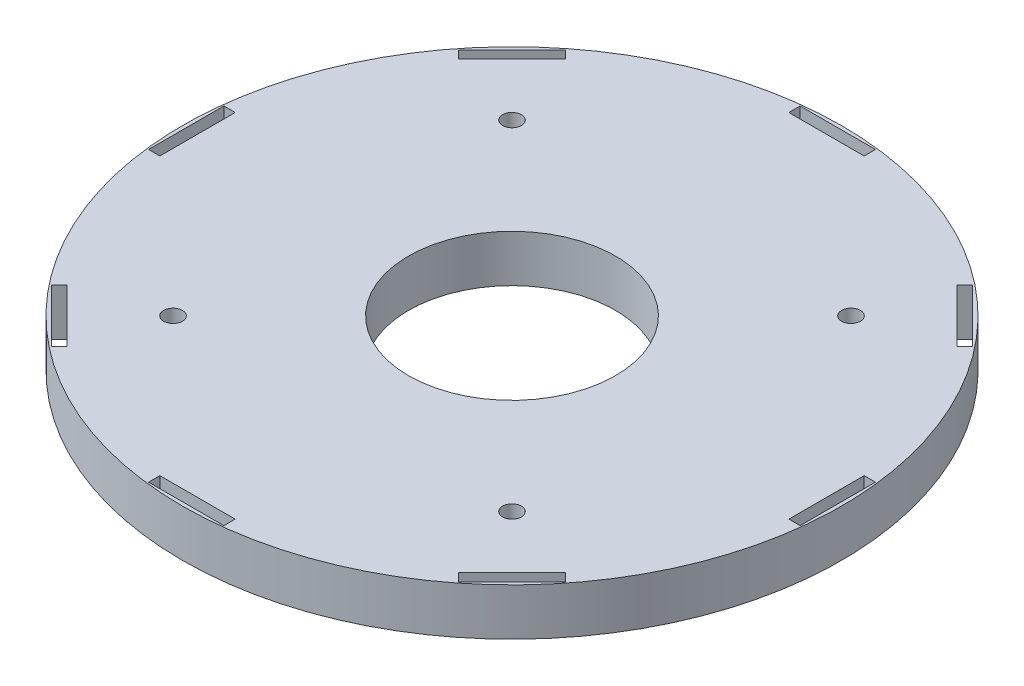
SolidWorks part; units mm, degrees
ref_plane "Front Plane" through (0, 0, 0) normal (0, 0, 1) x (1, 0, 0)
ref_plane "Top Plane" through (0, 0, 0) normal (0, 1, 0) x (1, 0, 0)
ref_plane "Right Plane" through (0, 0, 0) normal (1, 0, 0) x (0, 0, -1)
sketch "Sketch1" plane through (0, 0, 0) normal (0, 1, 0) x (1, 0, 0)
  circle A0 centre (0, 0) radius 175
  circle A1 centre (0, 0) radius 55
  dimension "D1" = 350
  dimension "D2" = 110
extrude "Boss-Extrude1" add sketch "Sketch1" along normal mid plane 25
sketch "Sketch2" plane through (0, 12.5, 0) normal (0, 1, 0) x (1, 0, 0)
  line L0 (0, 257.3432) -> (0, -227.7607) construction
  line L1 (-310.3726, 0) -> (339.0303, 0) construction
  line L3 (-20, 173) -> (20, 173)
  line L4 (-20, 173) -> (-20, 167)
  line L5 (-20, 167) -> (20, 167)
  line L6 (20, 173) -> (20, 167)
  line L7 (-20, 173) -> (20, 167) construction
  line L8 (-20, 167) -> (20, 173) construction
  line L30 (-160.5, -7.5) -> (-154.5, -7.5)
  line L31 (-160.5, 32.5) -> (-154.5, 32.5)
  line L36 (-160.5, -7.5) -> (-160.5, 32.5) [skipped]
  line L37 (-154.5, -7.5) -> (-154.5, 32.5) [skipped]
  line L38 (20, -142) -> (-20, -142) [skipped]
  line L39 (20, -148) -> (-20, -148) [skipped]
  line L40 (20, -148) -> (20, -142) [skipped]
  line L41 (-20, -148) -> (-20, -142) [skipped]
  line L42 (-95.1059, -110.8901) -> (-123.3901, -82.6059) [skipped]
  line L43 (-99.3485, -115.1328) -> (-127.6328, -86.8485) [skipped]
  line L44 (-99.3485, -115.1328) -> (-95.1059, -110.8901) [skipped]
  line L45 (-127.6328, -86.8485) -> (-123.3901, -82.6059) [skipped]
  line L46 (154.5, 32.5) -> (154.5, -7.5) [skipped]
  line L47 (160.5, 32.5) -> (160.5, -7.5) [skipped]
  line L48 (160.5, 32.5) -> (154.5, 32.5) [skipped]
  line L49 (160.5, -7.5) -> (154.5, -7.5) [skipped]
  line L50 (123.3901, -82.6059) -> (95.1059, -110.8901) [skipped]
  line L51 (127.6328, -86.8485) -> (99.3485, -115.1328) [skipped]
  line L52 (127.6328, -86.8485) -> (123.3901, -82.6059) [skipped]
  line L53 (99.3485, -115.1328) -> (95.1059, -110.8901) [skipped]
  line L54 (-123.3901, 107.6059) -> (-95.1059, 135.8901) [skipped]
  line L55 (-127.6328, 111.8485) -> (-99.3485, 140.1328) [skipped]
  line L56 (-127.6328, 111.8485) -> (-123.3901, 107.6059) [skipped]
  line L57 (-99.3485, 140.1328) -> (-95.1059, 135.8901) [skipped]
  line L58 (95.1059, 135.8901) -> (123.3901, 107.6059) [skipped]
  line L59 (99.3485, 140.1328) -> (127.6328, 111.8485) [skipped]
  line L60 (99.3485, 140.1328) -> (95.1059, 135.8901) [skipped]
  line L61 (127.6328, 111.8485) -> (123.3901, 107.6059) [skipped]
  line L62 (103.9447, 132.229) -> (132.229, 103.9447)
  line L63 (108.1873, 136.4716) -> (136.4716, 108.1873)
  line L64 (108.1873, 136.4716) -> (103.9447, 132.229)
  line L65 (136.4716, 108.1873) -> (132.229, 103.9447)
  line L66 (167, 20) -> (167, -20)
  line L67 (173, 20) -> (173, -20)
  line L68 (173, 20) -> (167, 20)
  line L69 (173, -20) -> (167, -20)
  line L70 (132.229, -103.9447) -> (103.9447, -132.229)
  line L71 (136.4716, -108.1873) -> (108.1873, -136.4716)
  line L72 (136.4716, -108.1873) -> (132.229, -103.9447)
  line L73 (108.1873, -136.4716) -> (103.9447, -132.229)
  line L74 (20, -167) -> (-20, -167)
  line L75 (20, -173) -> (-20, -173)
  line L76 (20, -173) -> (20, -167)
  line L77 (-20, -173) -> (-20, -167)
  line L78 (-103.9447, -132.229) -> (-132.229, -103.9447)
  line L79 (-108.1873, -136.4716) -> (-136.4716, -108.1873)
  line L80 (-108.1873, -136.4716) -> (-103.9447, -132.229)
  line L81 (-136.4716, -108.1873) -> (-132.229, -103.9447)
  line L82 (-167, -20) -> (-167, 20)
  line L83 (-173, -20) -> (-173, 20)
  line L84 (-173, -20) -> (-167, -20)
  line L85 (-173, 20) -> (-167, 20)
  line L86 (-132.229, 103.9447) -> (-103.9447, 132.229)
  line L87 (-136.4716, 108.1873) -> (-108.1873, 136.4716)
  line L88 (-136.4716, 108.1873) -> (-132.229, 103.9447)
  line L89 (-108.1873, 136.4716) -> (-103.9447, 132.229)
  point P5 (0, 170)
  point P41 (0, 12.5)
  point P98 (0, 0)
  dimension "D1" = 40
  dimension "D2" = 6
  dimension "D3" = 170
  dimension "D4" = 8
  dimension "D5" = 8
extrude "Cut-Extrude2" cut sketch "Sketch2" against normal through all contours L82 L85 L83 L84 | L87 L89 L86 L88 | L79 L81 L78 L80 | L5 L6 L3 L4 | L62 L65 L63 L64 | L66 L69 L67 L68 | L70 L73 L71 L72 | L74 L77 L75 L76
sketch "Sketch3" plane through (0, 12.5, 0) normal (0, 1, 0) x (1, 0, 0)
  line L0 (0, 231.3952) -> (0, -235.1527) construction
  line L1 (-294.3896, 0) -> (269.8232, 0) construction
  line L3 (-90, 90) -> (90, 90) construction
  line L4 (-90, 90) -> (-90, -90) construction
  line L5 (-90, -90) -> (90, -90) construction
  line L6 (90, 90) -> (90, -90) construction
  line L7 (-90, 90) -> (90, -90) construction
  line L8 (-90, -90) -> (90, 90) construction
  circle A0 centre (0, 0) radius 110 construction
  circle A1 centre (-90, 90) radius 5
  circle A2 centre (90, 90) radius 5
  circle A3 centre (90, -90) radius 5
  circle A4 centre (-90, -90) radius 5
  point P15 (0, 0)
  dimension "D1" = 220
  dimension "D4" = 90
  dimension "D5" = 10
  dimension "D2" = 180
  dimension "D3" = 180
extrude "Cut-Extrude3" cut sketch "Sketch3" against normal through all
